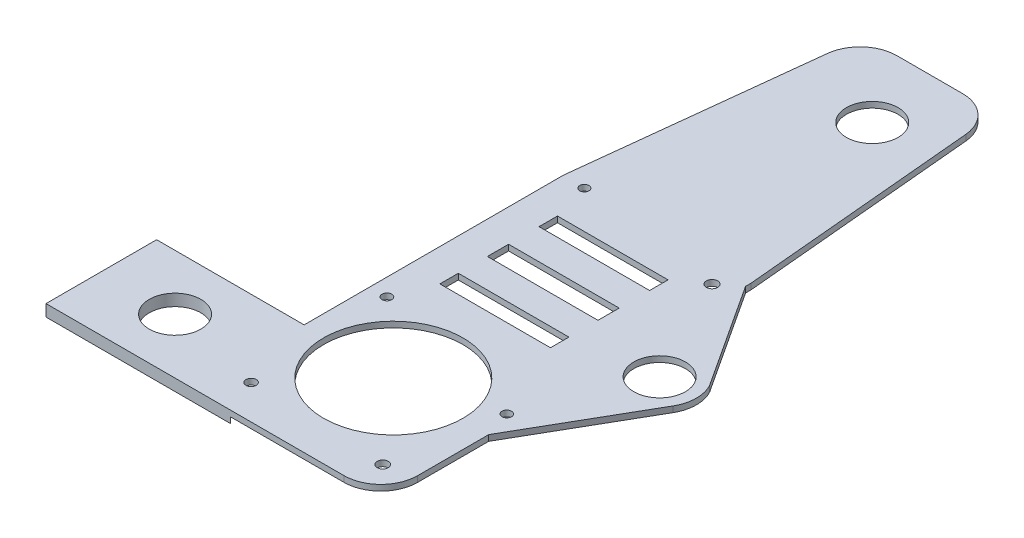
SolidWorks part; units mm, degrees
ref_plane "Front" through (0, 0, 0) normal (0, 0, 1) x (1, 0, 0)
ref_plane "Top" through (0, 0, 0) normal (0, 1, 0) x (1, 0, 0)
ref_plane "Right" through (0, 0, 0) normal (1, 0, 0) x (0, 0, -1)
sketch "Sketch1" plane through (0, 0, 0) normal (0, 1, 0) x (1, 0, 0)
  line L0 (10.4543, 228.6) -> (0, 135.3627)
  line L1 (0, 0) -> (50.8, 0)
  line L2 (0, 0) -> (0, 228.6)
  line L3 (0, 228.6) -> (50.8, 228.6)
  line L4 (50.8, 0) -> (50.8, 228.6)
  line L5 (42.3273, 228.6) -> (50.8, 135.3627)
  line L8 (50.8, 0) -> (24.327, 0)
  line L9 (50.8, 0) -> (50.8, -15)
  line L16 (50.8, 120.6192) -> (50.8, 104.4882)
  line L18 (50.8, 64.8791) -> (50.8, 87.4235)
  circle A12 centre (60.4, 101.001) radius 10
  circle A13 centre (29.5042, 189.5572) radius 7
  circle A15 centre (24.1018, 108.7849) radius 2.875
  dimension "D3" = 20
  dimension "D5" = 15
  dimension "D6" = 14
  dimension "D7" = 119.8151
  dimension "D1" = 50.8
  dimension "D2" = 228.6
extrude "Boss-Extrude1" add sketch "Sketch1" along normal blind 24.5875 contours L1 L4 L3 L0 L2
sketch "Sketch4" plane through (0, 0, -228.6) normal (0, 0, -1) x (-1, 0, 0)
  line L1 (-61.3109, 11.9192) -> (4.9615, 11.9192)
  line L2 (-61.3109, 11.9192) -> (-61.3109, -15.8811)
  line L3 (-61.3109, -15.8811) -> (4.9615, -15.8811)
  line L4 (4.9615, 11.9192) -> (4.9615, -15.8811)
extrude "Cut-Extrude2" cut sketch "Sketch4" against normal blind 20
fillet "Fillet3" radius 10 1 edges at (44.1447, 5.9596, -208.6)
fillet "Fillet4" radius 10 3 edges at (50.8, 12.2938, 0) (0, 12.2938, 0) (8.2118, 5.9596, -208.6)
sketch "Sketch6" plane through (0, 24.5875, 0) normal (0, 1, 0) x (1, 0, 0)
  line L0 (68.8909, 106.2834) -> (50.8, 135.3627)
  line L1 (50.8, 135.3627) -> (50.8, 103.801)
  line L2 (69.2582, 96.3607) -> (50.8, 61.1242)
  line L3 (50.8, 10) -> (50.8, 98.201) construction
  line L4 (50.8, 61.1242) -> (50.8, 96.3607)
  line L5 (50.8, 96.3607) -> (50.8, 98.201)
  circle A0 centre (60.4, 101.001) radius 10
extrude "Boss-Extrude3" add sketch "Sketch6" against normal blind 1.5875
sketch "Sketch7" plane through (0, 24.5875, 0) normal (0, 1, 0) x (1, 0, 0)
  circle A0 centre (60.4, 101.001) radius 7
  dimension "D1" = 14
extrude "Cut-Extrude3" cut sketch "Sketch7" against normal blind 1.5875
sketch "Sketch8" plane through (0, 24.5875, 0) normal (0, 1, 0) x (1, 0, 0)
  line L0 (35.0123, 208.6) -> (17.1532, 208.6) construction
  line L1 (9.492, 121.9099) -> (34.9257, 121.9099)
  line L2 (9.492, 121.9099) -> (9.492, 115.9099)
  line L3 (9.492, 115.9099) -> (34.9257, 115.9099)
  line L4 (34.9257, 121.9099) -> (34.9257, 115.9099)
  line L5 (9.492, 134.7849) -> (34.9257, 134.7849)
  line L6 (9.492, 134.7849) -> (9.492, 129.7849)
  line L7 (9.492, 129.7849) -> (34.9257, 129.7849)
  line L8 (34.9257, 134.7849) -> (34.9257, 129.7849)
  line L9 (9.492, 107.7849) -> (34.9257, 107.7849)
  line L10 (9.492, 107.7849) -> (9.492, 102.7849)
  line L11 (9.492, 102.7849) -> (34.9257, 102.7849)
  line L12 (34.9257, 107.7849) -> (34.9257, 102.7849)
  circle A0 centre (9.492, 118.9099) radius 3
  circle A1 centre (34.9257, 118.9099) radius 3
  circle A2 centre (23.3804, 122.2849) radius 2.5
  circle A4 centre (24.1018, 108.7849) radius 2.875 construction
  circle A5 centre (9.492, 132.2849) radius 2.5
  circle A6 centre (34.9257, 132.2849) radius 2.5
  circle A7 centre (24.29, 95.2849) radius 2.5
  circle A8 centre (24.1018, 108.7849) radius 2.875 construction
  circle A9 centre (9.492, 105.2849) radius 2.5
  circle A10 centre (34.9257, 105.2849) radius 2.5
  circle A11 centre (24.5838, 64.5939) radius 18.9
  circle M15 centre (24.1018, 108.7849) radius 2.875
  dimension "D1" = 13.5
  dimension "D2" = 13.5
  dimension "D3" = 73.8151
extrude "Cut-Extrude4" cut sketch "Sketch8" against normal blind 10 contours A1 L1 A0 L3 M15 | L2 A0 | L2 A0 | M15 | L4 A1 | L4 A1 | A5 L7 A2 L5 | A9 L11 A7 L9 | A10 L9 A7 L11 | A7 | A6
sketch "Sketch9" plane through (0, 0, 0) normal (0, -1, 0) x (1, 0, 0)
  line L1 (134.4567, -306.3857) -> (-94.6503, -306.3857)
  line L2 (134.4567, -306.3857) -> (134.4567, 54.8813)
  line L3 (134.4567, 54.8813) -> (-94.6503, 54.8813)
  line L4 (-94.6503, -306.3857) -> (-94.6503, 54.8813)
  circle A0 centre (6.3356, -44.2888) radius 1.3882
  circle A1 centre (43.4477, -42.8684) radius 1.4834
  circle A2 centre (4.6595, -82.7932) radius 1.3149
  circle A3 centre (48.401, -71.551) radius 1.2486
  circle A4 centre (5.8847, -135.1031) radius 1.2556
  circle A5 centre (45.7477, -129.8635) radius 1.5391
extrude "Cut-Extrude5" cut sketch "Sketch9" against normal blind 13
sketch "Sketch10" plane through (0, 24.5875, 0) normal (0, 1, 0) x (1, 0, 0)
  line L1 (8.7856, 124.9149) -> (38.774, 124.9149)
  line L2 (8.7856, 124.9149) -> (8.7856, 119.9149)
  line L3 (8.7856, 119.9149) -> (38.774, 119.9149)
  line L4 (38.774, 124.9149) -> (38.774, 119.9149)
  line L5 (8.7856, 111.6599) -> (38.774, 111.6599)
  line L6 (8.7856, 111.6599) -> (8.7856, 105.9099)
  line L7 (8.7856, 105.9099) -> (38.774, 105.9099)
  line L8 (38.774, 111.6599) -> (38.774, 105.9099)
  line L9 (8.7856, 98.0289) -> (38.774, 98.0289)
  line L10 (8.7856, 98.0289) -> (8.7856, 93.0289)
  line L11 (8.7856, 93.0289) -> (38.774, 93.0289)
  line L12 (38.774, 98.0289) -> (38.774, 93.0289)
  circle A0 centre (23.841, 122.4149) radius 2.5
  circle A1 centre (24.1018, 108.7849) radius 2.875 construction
  circle A2 centre (23.841, 95.5289) radius 2.5
  circle M1 centre (9.492, 118.9099) radius 3
  dimension "D1" = 13.63
extrude "Cut-Extrude6" cut sketch "Sketch10" against normal blind 22 contours A0 L1 L2 L3 M1 | A0 L3 L4 L1 | A0 | L8 L5 L6 L7 | A2 L9 L10 L11 | A2 L11 L12 L9 | A2 | L2 L3 M1
sketch "Sketch11" plane through (0, 24.5875, 0) normal (0, 1, 0) x (1, 0, 0)
  circle A0 centre (8.5355, 118.295) radius 5.2367
extrude "Cut-Extrude7" cut sketch "Sketch11" against normal blind 10
sketch "Sketch12" plane through (0, 14.5875, 0) normal (0, 1, 0) x (1, 0, 0)
  line L0 (50.8, 133.9005) -> (69.1954, 105.7592)
  line L1 (50.8, 103.801) -> (50.8, 135.3627) construction
  line L2 (69.0677, 96.0139) -> (50.8, 64.2642)
  line L3 (50.8, 10) -> (50.8, 98.201) construction
  line L4 (50.8, 64.2642) -> (50.8, 98.201)
  line L5 (50.8, 133.9005) -> (50.8, 103.801)
  circle A0 centre (60.4, 101.001) radius 10
  line M24 (50.8, 10) -> (50.8, 98.201)
  arc M25 (50.8, 98.201) -> (50.8, 103.801) centre (60.4, 101.001) cw
  line M26 (50.8, 103.801) -> (50.8, 135.3627)
extrude "Boss-Extrude4" add sketch "Sketch12" against normal blind 1.59 contours A0 L0 M26 | L0 A0 M25 | A0 L2 M24
sketch "Sketch13" plane through (0, 14.5875, 0) normal (0, 1, 0) x (1, 0, 0)
  circle A0 centre (60.4, 101.001) radius 7
extrude "Cut-Extrude8" cut sketch "Sketch13" against normal blind 41
sketch "Sketch14" plane through (0, 0, -228.6) normal (0, 0, -1) x (-1, 0, 0)
  line L1 (-2.551, 39.1752) -> (-64.0429, 39.1752)
  line L2 (-2.551, 39.1752) -> (-2.551, 3.5877)
  line L3 (-2.551, 3.5877) -> (-64.0429, 3.5877)
  line L4 (-64.0429, 39.1752) -> (-64.0429, 3.5877)
extrude "Cut-Extrude9" cut sketch "Sketch14" against normal blind 20
fillet "Fillet5" radius 10 2 edges at (8.2118, 13.7938, -208.6) (44.1447, 13.7938, -208.6)
sketch "Sketch16" plane through (0, 0, 0) normal (0, 0, 1) x (1, 0, 0)
  line L1 (-74.9257, 20.893) -> (88.7974, 20.893)
  line L2 (-74.9257, 20.893) -> (-74.9257, -1.979)
  line L3 (-74.9257, -1.979) -> (88.7974, -1.979)
  line L4 (88.7974, 20.893) -> (88.7974, -1.979)
extrude "Cut-Extrude11" cut sketch "Sketch16" against normal blind 35
fillet "Fillet6" radius 10 2 edges at (50.8, 13.7938, -35) (0, 13.7938, -35)
sketch "Sketch17" plane through (0, 0, 0) normal (0, -1, 0) x (1, 0, 0)
  circle A0 centre (45.7477, -129.8635) radius 1.5391
  circle A1 centre (5.8847, -135.1031) radius 1.2556
  circle A2 centre (48.401, -71.551) radius 1.3
  circle A3 centre (4.6595, -82.7932) radius 1.3149
  circle A4 centre (6.3356, -44.2888) radius 1.3882
  circle A5 centre (43.4477, -42.8684) radius 1.5
extrude "Cut-Extrude12" cut sketch "Sketch17" against normal blind 42
sketch "Sketch18" plane through (0, 24.5875, 0) normal (0, 1, 0) x (1, 0, 0)
  circle A0 centre (24.5838, 64.5939) radius 18.9
extrude "Cut-Extrude13" cut sketch "Sketch18" against normal blind 30
sketch "Sketch19" plane through (0, 14.5875, 0) normal (0, 1, 0) x (1, 0, 0)
  line L0 (0, 135.3627) -> (0, 45) construction
  line L1 (0, 65) -> (-40, 65)
  line L2 (0, 65) -> (0, 35)
  line L3 (0, 35) -> (-40, 35)
  line L4 (-40, 65) -> (-40, 35)
  line L5 (40.8, 35) -> (10, 35) construction
  line L6 (0, 35) -> (15.576, 35)
  line L7 (10, 35) -> (40.8, 35) construction
  circle A0 centre (-20, 50) radius 7
  line M37 (0, 135.3627) -> (0, 45)
  arc M38 (0, 45) -> (10, 35) centre (10, 45) ccw
  dimension "D1" = 14
  dimension "D2" = 0
  dimension "D3" = 30
  dimension "D4" = 15
  dimension "D5" = 20
  dimension "D6" = 40
extrude "Boss-Extrude5" add sketch "Sketch19" against normal blind 3.175 contours L1 L4 L3 L2 A0 M37 | L2 L6 M38
equation "\"7i\"=101.6"
